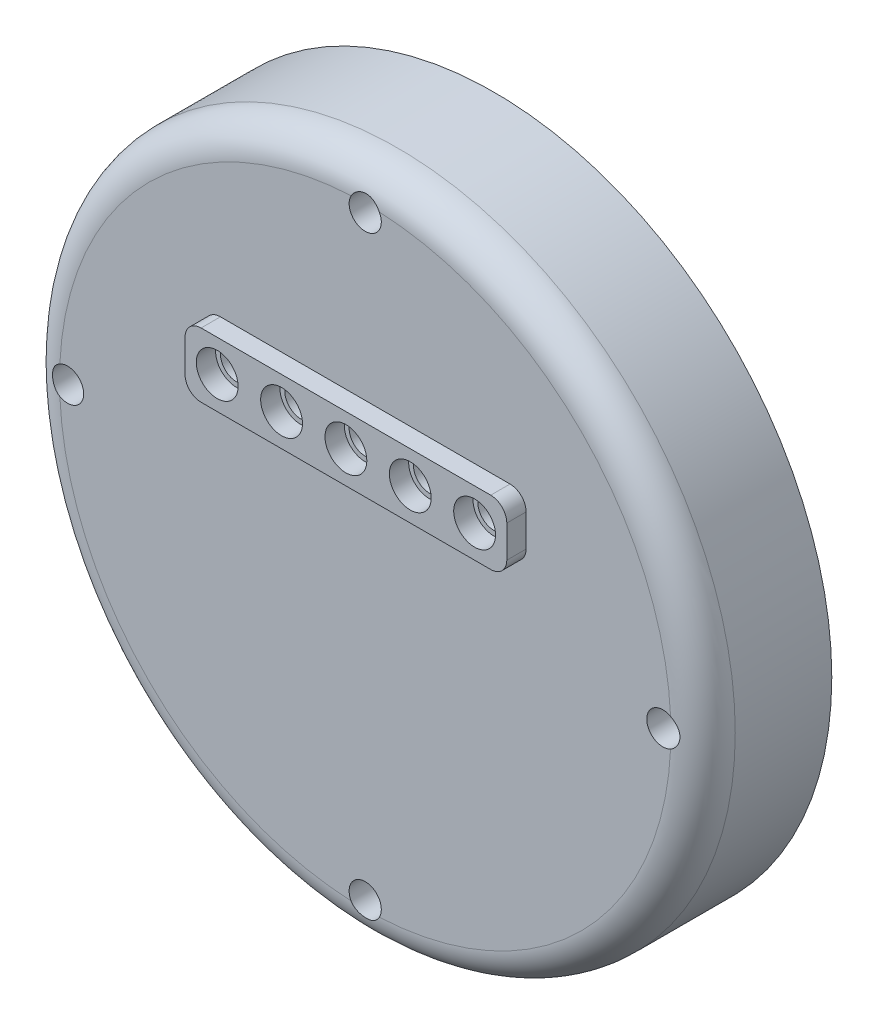
SolidWorks part; units mm, degrees
ref_plane "Front Plane" through (0, 0, 0) normal (0, 0, 1) x (1, 0, 0)
ref_plane "Top Plane" through (0, 0, 0) normal (0, 1, 0) x (1, 0, 0)
ref_plane "Right Plane" through (0, 0, 0) normal (1, 0, 0) x (0, 0, -1)
sketch "Sketch1" plane through (0, 0, 0) normal (0, 0, 1) x (1, 0, 0)
  circle A0 centre (0, 0) radius 52.5
  dimension "D1" = 105
extrude "Boss-Extrude1" add sketch "Sketch1" along normal blind 20
sketch "Sketch2" plane through (0, 0, 0) normal (0, 0, -1) x (-1, 0, 0)
  circle A0 centre (0, 0) radius 40
  circle A1 centre (0, 0) radius 42.5
  dimension "D1" = 85
  dimension "D2" = 80
extrude "Cut-Extrude1" cut sketch "Sketch2" against normal blind 7
sketch "Sketch3" plane through (0, 0, 0) normal (0, 0, -1) x (-1, 0, 0)
  line L0 (-20, -22) -> (20, -22)
  line L6 (-30, 6) -> (30, 6)
  line L7 (-20, -22) -> (-20, -25)
  line L8 (-20, -25) -> (20, -25)
  line L9 (20, -22) -> (20, -25)
  line L10 (-20, -22) -> (20, -25) construction
  line L11 (-20, -25) -> (20, -22) construction
  line L12 (-30, 6) -> (-30, 3)
  line L13 (-30, 3) -> (30, 3)
  line L14 (30, 6) -> (30, 3)
  line L15 (-30, 6) -> (30, 3) construction
  line L16 (-30, 3) -> (30, 6) construction
  point P0 (0, 4.5)
  point P6 (0, -23.5)
  dimension "D1" = 3
  dimension "D2" = 60
  dimension "D3" = 3
  dimension "D4" = 40
  dimension "D5" = 25
fillet "Fillet1" radius 5 1 edges at (52.5, 0, 20)
extrude "Cut-Extrude2" cut sketch "Sketch3" against normal blind 10
sketch "Sketch4" plane through (0, 0, 20) normal (0, 0, 1) x (1, 0, 0)
  circle A0 centre (0, 46.25) radius 2.5
  circle A1 centre (46.25, 0) radius 2.5
  circle A2 centre (0, -46.25) radius 2.5
  circle A3 centre (-46.25, 0) radius 2.5
  dimension "D5" = 5
  dimension "D6" = 5
  dimension "D7" = 5
  dimension "D8" = 5
  dimension "D1" = 46.25
  dimension "D2" = 46.25
  dimension "D3" = 46.25
  dimension "D4" = 46.25
extrude "Cut-Extrude3" cut sketch "Sketch4" against normal blind 5
sketch "Sketch5" plane through (0, 0, 15) normal (0, 0, 1) x (1, 0, 0)
  circle A1 centre (0, 46.25) radius 1.5
  dimension "D1" = 3
sketch "Sketch6" plane through (0, 0, 15) normal (0, 0, 1) x (1, 0, 0)
  circle A0 centre (46.25, 0) radius 1.5
  dimension "D1" = 3
sketch "Sketch7" plane through (0, 0, 15) normal (0, 0, 1) x (1, 0, 0)
  circle A0 centre (0, -46.25) radius 1.5
  dimension "D1" = 3
sketch "Sketch8" plane through (0, 0, 15) normal (0, 0, 1) x (1, 0, 0)
  circle A0 centre (-46.25, 0) radius 1.5
  dimension "D1" = 3
extrude "Cut-Extrude4" cut sketch "Sketch5" against normal blind 15 contours A1
extrude "Cut-Extrude5" cut sketch "Sketch8" against normal blind 15 contours A0
extrude "Cut-Extrude6" cut sketch "Sketch7" against normal blind 15 contours A0
extrude "Cut-Extrude7" cut sketch "Sketch6" against normal blind 15 contours A0
sketch "Sketch9" plane through (0, 0, 0) normal (0, 0, -1) x (-1, 0, 0)
  line L0 (-20, -25) -> (20, -25) construction
  line L1 (-1.5, -25) -> (1.5, -25)
  line L2 (-1.5, -25) -> (-1.5, -35)
  line L3 (-1.5, -35) -> (1.5, -35)
  line L4 (1.5, -25) -> (1.5, -35)
  line L7 (-20, -22) -> (-20, -25) construction
  dimension "D1" = 10
  dimension "D2" = 3
  dimension "D3" = 18.5
extrude "Cut-Extrude8" cut sketch "Sketch9" against normal blind 10
sketch "Sketch10" plane through (0, 0, 0) normal (0, 0, -1) x (-1, 0, 0)
  line L0 (30, 6) -> (-30, 6) construction
  circle A0 centre (-20, 16) radius 2.5
  circle A1 centre (-10, 16) radius 2.5
  circle A2 centre (0, 16) radius 2.5
  circle A3 centre (10, 16) radius 2.5
  circle A4 centre (20, 16) radius 2.5
  dimension "D1" = 5
  dimension "D2" = 5
  dimension "D4" = 5
  dimension "D5" = 5
  dimension "D6" = 5
  dimension "D3" = 10
  dimension "D7" = 10
  dimension "D8" = 10
  dimension "D9" = 10
  dimension "D10" = 10
extrude "Cut-Extrude9" cut sketch "Sketch10" against normal blind 20
sketch "Sketch11" plane through (0, 0, 20) normal (0, 0, 1) x (1, 0, 0)
  line L1 (-25, 21) -> (25, 21)
  line L2 (-25, 21) -> (-25, 11)
  line L3 (-25, 11) -> (25, 11)
  line L4 (25, 21) -> (25, 11)
  line L5 (-25, 21) -> (25, 11) construction
  line L6 (-25, 11) -> (25, 21) construction
  circle A0 centre (-20, 16) radius 3.25
  circle A1 centre (-10, 16) radius 3.25
  circle A2 centre (0, 16) radius 3.25
  circle A3 centre (10, 16) radius 3.25
  circle A4 centre (20, 16) radius 3.25
  point P0 (0, 16)
  dimension "D3" = 6.5
  dimension "D4" = 6.5
  dimension "D5" = 6.5
  dimension "D6" = 6.5
  dimension "D7" = 6.5
  dimension "D1" = 50
  dimension "D2" = 10
extrude "Boss-Extrude2" add sketch "Sketch11" along normal blind 3
fillet "Fillet2" radius 2.5 4 edges at (-25, 11, 21.5) (-25, 21, 21.5) (25, 11, 21.5) (25, 21, 21.5)
